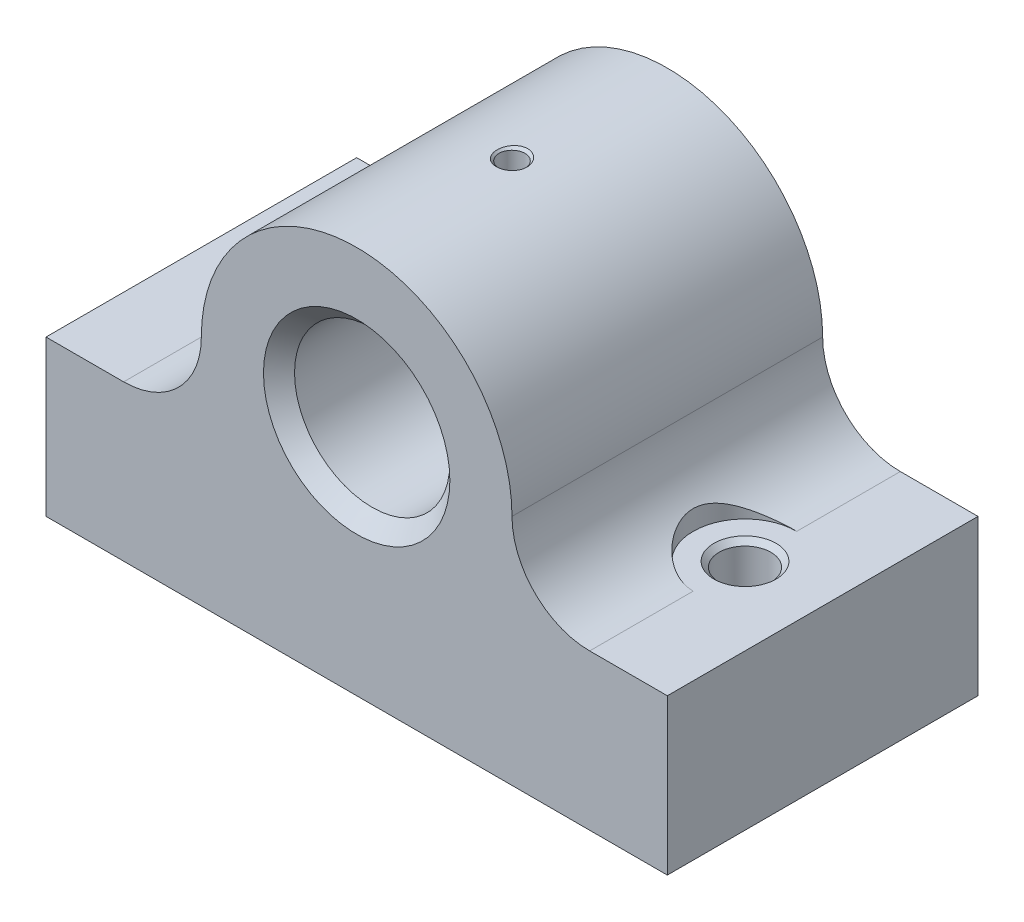
SolidWorks part; units mm, degrees
ref_plane "Front Plane" through (0, 0, 0) normal (0, 0, 1) x (1, 0, 0)
ref_plane "Top Plane" through (0, 0, 0) normal (0, 1, 0) x (1, 0, 0)
ref_plane "Right Plane" through (0, 0, 0) normal (1, 0, 0) x (0, 0, -1)
sketch "Sketch1" plane through (0, 0, 0) normal (0, 1, 0) x (1, 0, 0)
  line L1 (60, 30) -> (-60, 30)
  line L2 (60, 30) -> (60, -30)
  line L3 (60, -30) -> (-60, -30)
  line L4 (-60, 30) -> (-60, -30)
  line L5 (60, 30) -> (-60, -30) construction
  line L6 (60, -30) -> (-60, 30) construction
  point P0 (0, 0)
  dimension "D1" = 120
  dimension "D2" = 60
extrude "Boss-Extrude1" add sketch "Sketch1" along normal blind 30
sketch "Sketch2" plane through (0, 0, 30) normal (0, 0, 1) x (1, 0, 0)
  line L0 (-60, 30) -> (60, 30) construction
  circle A0 centre (0, 45) radius 30
  dimension "D2" = 60
  dimension "D1" = 15
extrude "Boss-Extrude2" add sketch "Sketch2" against normal blind 60
sketch "Sketch3" plane through (0, 0, 30) normal (0, 0, 1) x (1, 0, 0)
  circle A0 centre (0, 45) radius 15
  dimension "D1" = 30
extrude "Cut-Extrude1" cut sketch "Sketch3" against normal through all
chamfer "Chamfer1" distance 3 angle 45 2 edges at (15, 45, 30) (15, 45, -30)
fillet "Fillet2" radius 15 2 edges at (25.9808, 30, 0) (-25.9808, 30, 0)
sketch "Sketch4" plane through (0, 30, 0) normal (0, 1, 0) x (1, 0, 0)
  line L0 (-45, -30) -> (-45, 30) construction
  line L1 (45, 30) -> (45, -30) construction
  circle A0 centre (-45, 0) radius 10
  circle A1 centre (45, 0) radius 10
  dimension "D1" = 20
  dimension "D2" = 20
extrude "Cut-Extrude2" cut sketch "Sketch4" along normal blind 5
sketch "Sketch5" plane through (0, 30, 0) normal (0, 1, 0) x (1, 0, 0)
  circle A0 centre (-45, 0) radius 5
  circle A1 centre (45, 0) radius 5
  dimension "D1" = 10
extrude "Cut-Extrude3" cut sketch "Sketch5" against normal through all
chamfer "Chamfer2" distance 1 angle 45 2 edges at (45, 30, 5) (-45, 30, 5)
ref_plane "Plane1" through (0, 75, 0) normal (0, 1, 0) x (1, 0, 0)
hole_wizard "M6 Tapped Hole2" positions "Sketch8" profile "Sketch6" tap size "M6" standard "ISO"
sketch "Sketch8" plane through (0, 75, 0) normal (0, 1, 0) x (1, 0, 0)
  point P5 (0, 0)
sketch "Sketch6" plane through (0, 75, 0) normal (1, 0, 0) x (0, 0, 1)
  line L0 (0, 0) -> (0, 31.5012)
  line L1 (0, 31.5012) -> (2.5, 29.999)
  line L2 (2.5, 29.999) -> (2.5, 0.525)
  line L3 (2.5, 0.525) -> (3.025, 0)
  line L5 (3.025, 0) -> (0, 0)
  line L6 (-2.5, 0.525) -> (-3.025, 0) construction
  line L10 (0, 31.5012) -> (-2.5, 29.999) construction
  line L11 (0, -6.35) -> (0, 107.95) construction
  dimension "Tap Drill Dia." = 5
  dimension "Tap Drill Depth" = 29.999
  dimension "Near C'Sink Dia." = 6.05
  dimension "Near C'Sink Angle" = 90
  dimension "Drill Angle" = 118
cosmetic thread "Hole Thread1" parameters "D1"=14.81, "D2"=6
